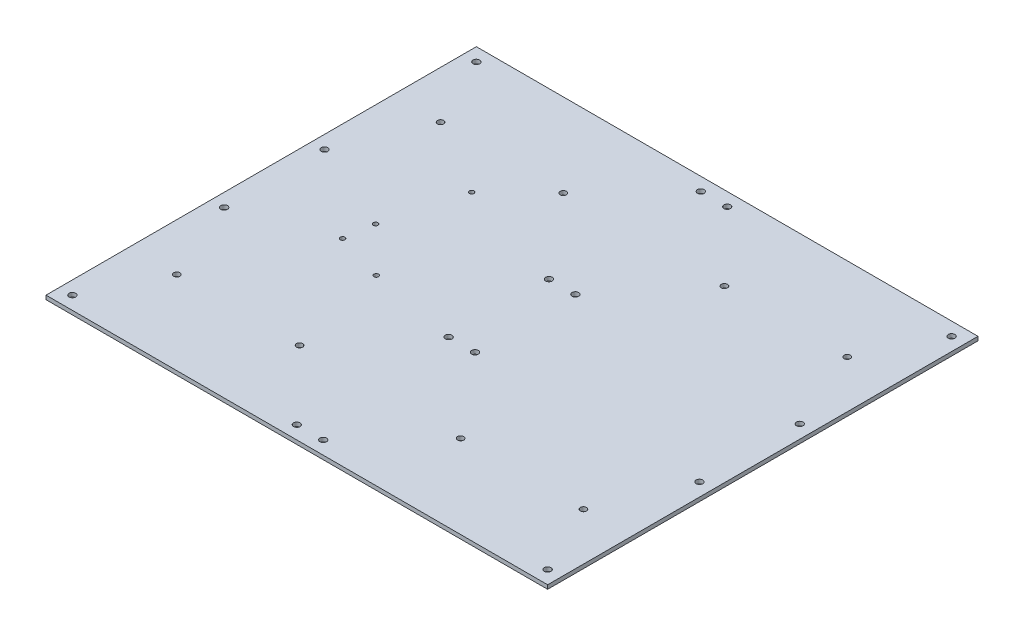
SolidWorks part; units mm, degrees
ref_plane "Ebene vorne" through (0, 0, 0) normal (0, 0, 1) x (1, 0, 0)
ref_plane "Ebene oben" through (0, 0, 0) normal (0, 1, 0) x (1, 0, 0)
ref_plane "Ebene rechts" through (0, 0, 0) normal (1, 0, 0) x (0, 0, -1)
sketch "Skizze1" plane through (0, 0, 0) normal (0, 1, 0) x (1, 0, 0)
  line L1 (190, -163) -> (-190, -163)
  line L2 (190, -163) -> (190, 163)
  line L3 (190, 163) -> (-190, 163)
  line L4 (-190, -163) -> (-190, 163)
  line L5 (190, -163) -> (-190, 163) construction
  line L6 (190, 163) -> (-190, -163) construction
  point P0 (0, 0)
  dimension "D1" = 326
  dimension "D2" = 380
  dimension "D3" = 326
extrude "Aufsatz-Linear austragen1" add sketch "Skizze1" along normal blind 3
sketch "Skizze2" plane through (0, 3, 0) normal (0, 1, 0) x (1, 0, 0)
  line L0 (-190, 153) -> (190, 153) construction
  line L1 (-190, 163) -> (-190, -163) construction
  line L2 (190, -163) -> (190, 163) construction
  line L3 (190, 163) -> (-190, 163) construction
  line L4 (-190, -153) -> (190, -153) construction
  line L5 (-180, 163) -> (-180, -163) construction
  line L6 (-190, -163) -> (190, -163) construction
  line L7 (180, 163) -> (180, -163) construction
  line L8 (-10, 163) -> (-10, -163) construction
  line L9 (10, 163) -> (10, -163) construction
  line L10 (-180, 38) -> (180, 38) construction
  line L11 (-180, -38) -> (180, -38) construction
  circle A0 centre (-180, 153) radius 2.5
  circle A1 centre (180, 153) radius 2.5
  circle A4 centre (-180, -153) radius 2.5
  circle A5 centre (180, -153) radius 2.5
  circle A6 centre (-10, 153) radius 2.5
  circle A7 centre (10, 153) radius 2.5
  circle A8 centre (-10, 38) radius 2.5
  circle A9 centre (10, 38) radius 2.5
  circle A10 centre (-10, -38) radius 2.5
  circle A11 centre (10, -38) radius 2.5
  circle A12 centre (-10, -153) radius 2.5
  circle A13 centre (10, -153) radius 2.5
  circle A14 centre (-180, 38) radius 2.5
  circle A15 centre (-180, -38) radius 2.5
  circle A16 centre (180, 38) radius 2.5
  circle A17 centre (180, -38) radius 2.5
  dimension "D4" = 5
  dimension "D1" = 10
  dimension "D2" = 10
  dimension "D3" = 10
  dimension "D5" = 170
  dimension "D6" = 170
  dimension "D7" = 115
  dimension "D8" = 115
  dimension "D9" = 10
extrude "Schnitt-Linear austragen1" cut sketch "Skizze2" against normal through all
sketch "Skizze3" plane through (0, 3, 0) normal (0, 1, 0) x (1, 0, 0)
  line L0 (-190, 99.9) -> (190, 99.9) construction
  line L3 (-190, 163) -> (-190, -163) construction
  line L6 (190, -163) -> (190, 163) construction
  line L7 (190, 163) -> (-190, 163) construction
  line L8 (-190, -99.9) -> (190, -99.9) construction
  line L9 (-190, -163) -> (190, -163) construction
  line L10 (-154, 163) -> (-154, -163) construction
  line L11 (-61, 163) -> (-61, -163) construction
  line L12 (61, 163) -> (61, -163) construction
  line L13 (154, 163) -> (154, -163) construction
  circle A15 centre (61, 99.9) radius 2.35
  circle A16 centre (154, 99.9) radius 2.35
  circle A17 centre (-154, -99.9) radius 2.35
  circle A18 centre (-61, -99.9) radius 2.35
  circle A20 centre (154, -99.9) radius 2.35
  circle A21 centre (61, -99.9) radius 2.35
  circle A22 centre (-154, 99.9) radius 2.35
  circle A23 centre (-61, 99.9) radius 2.35
  dimension "D1" = 63.1
  dimension "D5" = 93
  dimension "D6" = 93
  dimension "D7" = 4.7
  dimension "D2" = 63.1
  dimension "D3" = 36
  dimension "D4" = 36
extrude "Schnitt-Linear austragen2" cut sketch "Skizze3" against normal through all
sketch "Skizze4" plane through (0, 3, 0) normal (0, 1, 0) x (1, 0, 0)
  line L0 (-190, 0) -> (190, 0) construction
  line L1 (-49.839, -67.5) -> (-139.839, -67.5) construction
  line L2 (-49.839, -67.5) -> (-49.839, 67.5) construction
  line L3 (-49.839, 67.5) -> (-139.839, 67.5) construction
  line L4 (-139.839, -67.5) -> (-139.839, 67.5) construction
  line L5 (-49.839, -67.5) -> (-139.839, 67.5) construction
  line L6 (-49.839, 67.5) -> (-139.839, -67.5) construction
  line L7 (-190, 163) -> (-190, -163) construction
  line L8 (190, -163) -> (190, 163) construction
  circle A0 centre (-114.839, -13.5) radius 1.75
  circle A1 centre (-77.839, -25) radius 1.75
  circle A2 centre (-111.839, 8.5) radius 1.75
  circle A3 centre (-96.339, 65.75) radius 1.75
  point P0 (-94.839, 0)
  dimension "D3" = 59
  dimension "D9" = 3.5
  dimension "D11" = 3.5
  dimension "D1" = 135
  dimension "D2" = 90
  dimension "D4" = 81
  dimension "D5" = 25
  dimension "D6" = 28
  dimension "D7" = 92.5
  dimension "D8" = 62
  dimension "D10" = 43.5
extrude "Schnitt-Linear austragen3" cut sketch "Skizze4" against normal through all
equation "\"D2@Skizze2\"=\"D1@Skizze2\""
equation "\"D3@Skizze1\"=\"D1@Skizze1\""
equation "\"D6@Skizze2\"=\"D5@Skizze2\""
